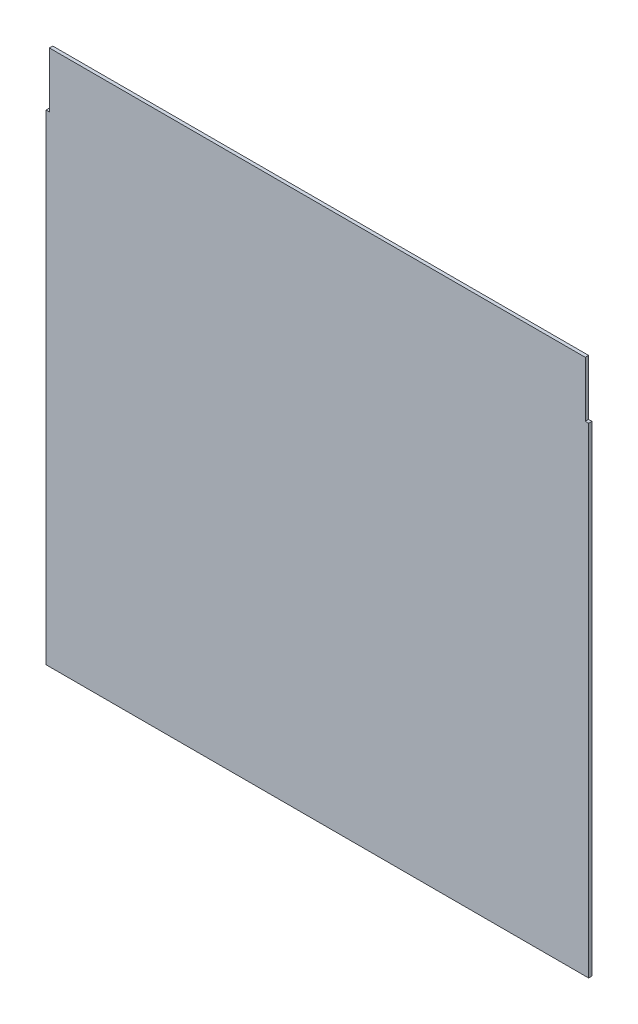
SolidWorks part; units mm, degrees
ref_plane "Front Plane" through (0, 0, 0) normal (0, 0, 1) x (1, 0, 0)
ref_plane "Top Plane" through (0, 0, 0) normal (0, 1, 0) x (1, 0, 0)
ref_plane "Right Plane" through (0, 0, 0) normal (1, 0, 0) x (0, 0, -1)
sketch "Sketch1" plane through (0, 0, 0) normal (0, 0, 1) x (1, 0, 0)
  line L1 (-254, -254) -> (254, -254)
  line L2 (-254, -254) -> (-254, 254)
  line L3 (-254, 254) -> (254, 254)
  line L4 (254, -254) -> (254, 254)
  line L5 (-254, -254) -> (254, 254) construction
  line L6 (-254, 254) -> (254, -254) construction
  point P0 (0, 0)
  dimension "D1" = 508
  dimension "D2" = 508
extrude "Boss-Extrude1" add sketch "Sketch1" along normal blind 3.175
sketch "Sketch3" plane through (0, 0, 3.175) normal (0, 0, 1) x (1, 0, 0)
  line L0 (-254, 254) -> (-254, -254) construction
  line L1 (-46.99, 140.97) -> (-39.37, 140.97)
  line L2 (-46.99, 140.97) -> (-46.99, 160.02)
  line L3 (-46.99, 160.02) -> (-39.37, 160.02)
  line L4 (-39.37, 140.97) -> (-39.37, 160.02)
  line L5 (254, 254) -> (-254, 254) construction
  dimension "D1" = 207.01
  dimension "D2" = 7.62
  dimension "D3" = 113.03
  dimension "D4" = 19.05
extrude "Cut-Extrude2" [suppressed] cut sketch "Sketch3" against normal up to surface (3.175 mm away)
sketch "Sketch2" [suppressed] plane through (0, 0, 3.175) normal (0, 0, 1) x (1, 0, 0)
  line L0 (-250.825, 190.5) -> (-250.825, -190.5) construction
  line L1 (254, 190.5) -> (-254, 190.5) construction
  line L2 (-254, -190.5) -> (254, -190.5) construction
  line L3 (250.825, 190.5) -> (250.825, -190.5) construction
  line L4 (254, -190.5) -> (254, 190.5) construction
  line L5 (-254, 190.5) -> (-254, -190.5) construction
  line L6 (0, 0) -> (0, -50000) construction
  line L8 (-39.37, 96.52) -> (-46.99, 96.52) construction
  circle A0 centre (-250.825, -184.15) radius 1.8542
  circle A1 centre (-250.825, 184.15) radius 1.8542
  circle A2 centre (250.825, 184.15) radius 1.8542
  circle A3 centre (250.825, -184.15) radius 1.8542
  circle A4 centre (-250.825, 24.13) radius 1.8542
  circle A5 centre (250.825, 24.13) radius 1.8542
  circle A6 centre (-250.825, 11.43) radius 1.8542
  circle A7 centre (-250.825, -148.59) radius 1.8542
  circle A8 centre (-250.825, -161.29) radius 1.8542
  circle A9 centre (250.825, -161.29) radius 1.8542
  circle A10 centre (250.825, -148.59) radius 1.8542
  circle A11 centre (250.825, 11.43) radius 1.8542
  circle A12 centre (-79.7747, 110.49) radius 1.905
  circle A13 centre (-79.7747, 41.91) radius 1.905
  circle A14 centre (-61.9947, 110.49) radius 1.905
  circle A15 centre (-61.9947, 41.91) radius 1.905
  point P33 (0, -190.5)
  dimension "D3" = 3.7084
  dimension "D10" = 12.7
  dimension "D14" = 3.81
  dimension "D12" = 17.78
  dimension "D1" = 3.175
  dimension "D2" = 3.175
  dimension "D4" = 6.35
  dimension "D5" = 6.35
  dimension "D6" = 6.35
  dimension "D7" = 6.35
  dimension "D8" = 160.02
  dimension "D9" = 160.02
  dimension "D11" = 29.21
  dimension "D13" = 68.58
  dimension "D15" = 15.0047
  dimension "D16" = 13.97
extrude "Cut-Extrude1" [suppressed] cut sketch "Sketch2" against normal blind 3.175
sketch "Sketch4" plane through (0, 0, 3.175) normal (0, 0, 1) x (1, 0, 0)
  line L0 (254, -254) -> (254, 254) construction
  line L1 (254, 201.4538) -> (257.175, 201.4538)
  line L2 (254, 201.4538) -> (254, -254)
  line L3 (254, -254) -> (257.175, -254)
  line L4 (257.175, 201.4538) -> (257.175, -254)
  line L5 (-254, -254) -> (254, -254) construction
  line L6 (254, 254) -> (-254, 254) construction
  line L7 (0, 254) -> (0, -254) construction
  line L8 (-254, -254) -> (-257.175, -254)
  line L9 (-254, 201.4537) -> (-257.175, 201.4537)
  line L10 (-254, 201.4537) -> (-254, -254)
  line L11 (-257.175, 201.4537) -> (-257.175, -254)
  dimension "D1" = 3.175
  dimension "D2" = 52.5463
extrude "Boss-Extrude2" add sketch "Sketch4" against normal blind 3.175
